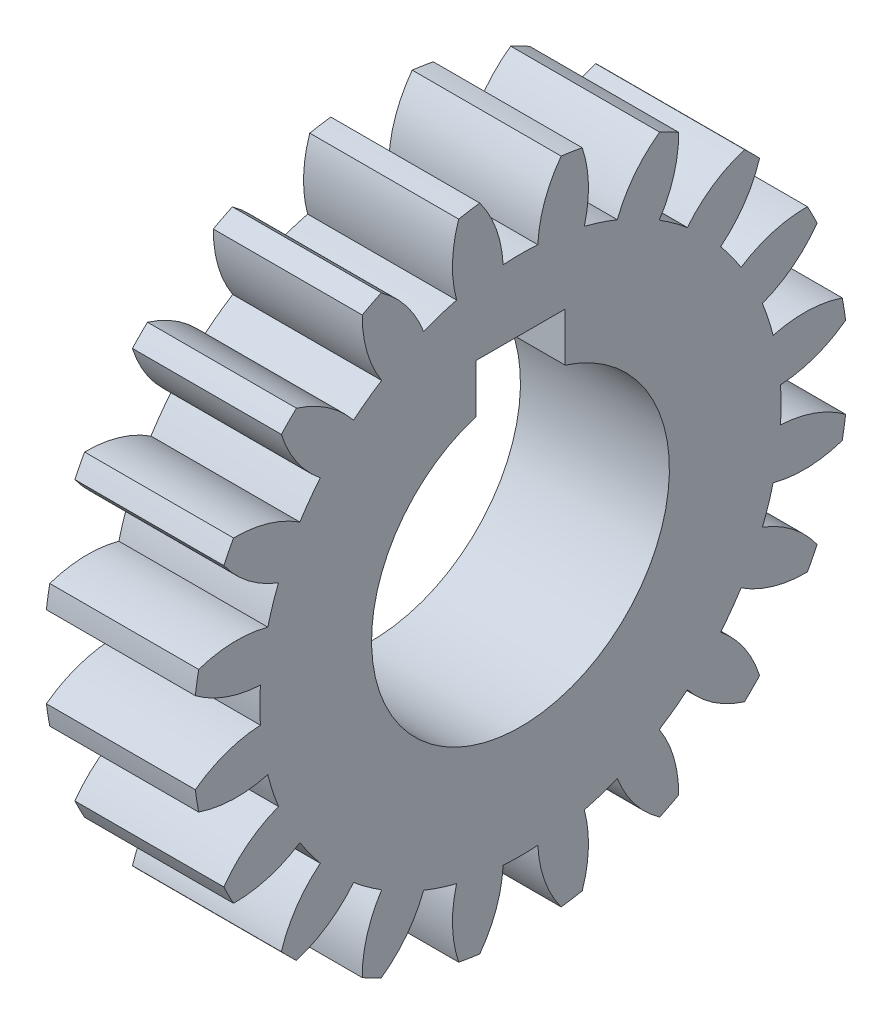
SolidWorks part; units mm, degrees
ref_plane "Plane1" through (0, 0, 0) normal (0, 0, 1) x (1, 0, 0)
ref_plane "Plane2" through (0, 0, 0) normal (0, 1, 0) x (1, 0, 0)
ref_plane "Plane3" through (0, 0, 0) normal (1, 0, 0) x (0, 0, -1)
sketch "HoldingSke" plane through (0, 0, 0) normal (0, 1, 0) x (1, 0, 0)
  line L0 (0, 0) -> (0.4698, -0.171)
  line L1 (-15, 0) -> (100, 0) construction
  line L2 (0, 0) -> (-2.1039, 2.3779)
  line L3 (0, 0) -> (-11.863, 4.5341)
  line L4 (0, 0) -> (8.1152, 2.9537)
  line L5 (0, 0) -> (-46.8476, -17.4728)
  line L6 (0, 0) -> (-8.2896, -5.593)
  line L7 (-2.1039, 2.3779) -> (8.6586, 51.2059)
  line L8 (-76.2, 54.61) -> (-73.4, 54.61)
  line L9 (-67.7845, 28.3722) -> (-49.3413, 33.142)
  line L10 (-76.2, 71.12) -> (104.1128, 71.12)
  line L11 (0, 0) -> (-10, 0)
  line L12 (-76.2, 101.6) -> (-76.133, 101.6)
  line L13 (24.9733, 27.94) -> (52.9518, 28.4284)
  line L14 (24.9733, 27.94) -> (24.9743, 27.94)
  line L15 (24.9733, 27.94) -> (100.4006, 29.5858)
  line L16 (-63.627, -2) -> (-12.827, -2)
  circle A0 centre (0, 0) radius 10
  circle A1 centre (0, 0) radius 17.499
  circle A2 centre (0, 0) radius 37.5
  circle A3 centre (0, 0) radius 10
  dimension "MHD" = 34.998
  dimension "Hub_dia" = 75
  dimension "Bore" = 20
  dimension "MBD" = 20
  dimension "Num_teeth" = 20
  dimension "Pitch" = 0.5
  dimension "Overall_len" = 50
  dimension "Show_teeth" = 20
  dimension "Thickness" = 10
  dimension "OAL" = 50.0001
  dimension "T_dim" = 2.8
  dimension "Ap" = 14.5
  dimension "H" = 19.05
  dimension "Pitch_radius" = 180.3128
  dimension "Width" = 10
  dimension "Backlash" = 0.067
  dimension "Addendum_fac" = 1
  dimension "Dedendum_fac" = 1.25
  dimension "Clearance_fac" = 0.25
  dimension "Dedendum_add" = 0.001
  dimension "Module" = 2
sketch "BasProSke" plane through (0, 0, 0) normal (0, 1, 0) x (1, 0, 0)
  line L0 (-10, 0) -> (60, 0) construction
  line L1 (0, 0) -> (0, 22)
  line L2 (0, 0) -> (10, 0)
  line L3 (10, 0) -> (10, 22)
  line L4 (10, 22) -> (0, 22)
  dimension "Thickness" = 10
  dimension "Diameter" = 44
revolve "Base-Revolve" add sketch "BasProSke" angle 360 about L0
sketch "TooCutSke" plane through (0, 0, 0) normal (1, 0, 0) x (0, 0, -1)
  line L1 (0, 0) -> (0, 107) construction
  line L2 (0, 0) -> (-1.6864, 19.9288) construction
  line L3 (0, 0) -> (-6.2409, 39.4033) construction
  line L4 (-1.6864, 19.9288) -> (-3.1204, 19.7016) construction
  arc A0 (1.165, 17.4602) -> (-1.165, 17.4602) centre (0, 0) ccw
  arc A1 (2.7485, 21.8532) -> (-2.7485, 21.8532) centre (0, 0) ccw
  circle A2 centre (0, 0) radius 20 construction
  circle A3 centre (0, 0) radius 19.363 construction
  arc A4 (-1.165, 17.4602) -> (-2.7485, 21.8532) centre (-9.1551, 17.0619) ccw
  arc A5 (2.7485, 21.8532) -> (1.165, 17.4602) centre (9.1551, 17.0619) ccw
  dimension "Root_dia" = 34.998
  dimension "Overcut_dia" = 44.0508
  dimension "Pitch_dia" = 40
  dimension "Base_dia" = 38.7259
  dimension "Flank_rad" = 8
  dimension "Half_ang" = 9
  dimension "Half_CT" = 1.4519
extrude "ToothCut" cut sketch "TooCutSke" along normal through all
fillet "Breaks" [suppressed] radius 0.04
fillet "RootFillets" [suppressed] radius 0.501
pattern_circular "TeethCuts" count 20 every 18 about axis through (-10, 0, 0) along (1, 0, 0) of "ToothCut", "RootFillets", "Breaks"
sketch "HubNeaOneSke" plane through (0, 0, 0) normal (-1, 0, 0) x (0, 0, 1)
  circle A0 centre (0, 0) radius 17.499
  dimension "Diameter" = 34.998
extrude "HubNearOne" [suppressed] add sketch "HubNeaOneSke" along normal blind 40.0001
sketch "HubNeaBotSke" plane through (0, 0, 0) normal (-1, 0, 0) x (0, 0, 1)
  circle A0 centre (0, 0) radius 17.499
  dimension "Diameter" = 34.998
extrude "HubNearBoth" [suppressed] add sketch "HubNeaBotSke" along normal blind 20
ref_plane "FarPln" through (10, 0, 0) normal (1, 0, 0) x (0, 0, -1)
sketch "HubFarSke" plane through (10, 0, 0) normal (1, 0, 0) x (0, 0, -1)
  circle A0 centre (0, 0) radius 17.499
  dimension "Diameter" = 34.998
extrude "HubFar" [suppressed] add sketch "HubFarSke" along normal blind 20
sketch "BorSke" plane through (0, 0, 0) normal (1, 0, 0) x (0, 0, -1)
  circle A0 centre (0, 0) radius 10
  dimension "Diameter" = 20
extrude "Bore" cut sketch "BorSke" along normal mid plane 100.0001
sketch "KeySke" plane through (0, 0, 0) normal (1, 0, 0) x (0, 0, -1)
  line L0 (-3, 0) -> (-3, 12.8)
  line L1 (-3, 12.8) -> (3, 12.8)
  line L2 (3, 12.8) -> (3, 0)
  line L3 (0, 0) -> (0, 34) construction
  line L4 (-3, 0) -> (3, 0)
  dimension "Offset" = 12.8
  dimension "Width" = 6
extrude "Keyway" cut sketch "KeySke" along normal mid plane 100.0001
pattern_circular "Keyway2" [suppressed] count 2 every 90 about axis through (-10, 0, 0) along (1, 0, 0)
equation "' \"Module@HoldingSke\" = 6.35"
equation "' \"Num_teeth@HoldingSke\" = 12"
equation "' \"Ap@HoldingSke\" =  20"
equation "' \"Ap@HoldingSke\" = 20"
equation "' \"Width@HoldingSke\" = 0.5 * 25.4"
equation "' \"Hub_dia@HoldingSke\"= 1 * 25.4"
equation "' \"Hub_dia@HoldingSke\" = 1 * 25.4"
equation "' \"Overall_len@HoldingSke\" = 1.0 * 25.4"
equation "' \"Bore@HoldingSke\" = 0.75 * 25.4"
equation "' \"T_dim@HoldingSke\" = 0.1 * 25.4"
equation "' \"Width@KeySke\" = 0.25 * 25.4"
equation "' \"Show_teeth@HoldingSke\" = 13"
equation "' \"Backlash@HoldingSke\" = 0.009 * 25.4"
equation "' \"Addendum_fac@HoldingSke\" = 1.0"
equation "' \"Dedendum_fac@HoldingSke\" = 1.25"
equation "' \"Dedendum_add@HoldingSke\" = 0.00005 * 25.4"
equation "' \"Clearance_fac@HoldingSke\" = 0.25"
equation "\"Pitch@HoldingSke\" = 1 / \"Module@HoldingSke\""
equation "\"Overcut_dia@TooCutSke\" = (\"Num_teeth@HoldingSke\" + 2 * \"Addendum_fac@HoldingSke\") / \"Pitch@HoldingSke\" + 0.002 * 25.4"
equation "\"Pitch_dia@TooCutSke\" = \"Num_teeth@HoldingSke\" / \"Pitch@HoldingSke\""
equation "\"Base_dia@TooCutSke\" = \"Num_teeth@HoldingSke\" / \"Pitch@HoldingSke\" * cos((\"Ap@HoldingSke\"  * 3.14159265 / 180))"
equation "\"Root_dia@TooCutSke\" = (\"Num_teeth@HoldingSke\" + 2) / \"Pitch@HoldingSke\" - 2 * (\"Addendum_fac@HoldingSke\" + \"Dedendum_fac@HoldingSke\") / \"Pitch@HoldingSke\" - \"Dedendum_add@HoldingSke\" * 2"
equation "\"Half_ang@TooCutSke\" = 180 / \"Num_teeth@HoldingSke\""
equation "\"Half_CT@TooCutSke\" = \"Num_teeth@HoldingSke\" / \"Pitch@HoldingSke\" * sin((3.14159265 / 2 / \"Num_teeth@HoldingSke\")) / 2 - 7 * \"Backlash@HoldingSke\" / 4"
equation "\"Flank_rad@TooCutSke\" = \"Num_teeth@HoldingSke\" / \"Pitch@HoldingSke\" / 5"
equation "\"Radius@RootFillets\" = \"Clearance_fac@HoldingSke\" / \"Pitch@HoldingSke\" + \"Dedendum_add@HoldingSke\""
equation "\"Break_rad@Breaks\" = 0.02 / \"Pitch@HoldingSke\""
equation "\"Thickness@HoldingSke\" = \"Width@HoldingSke\""
equation "\"OAL@HoldingSke\" = \"Thickness@HoldingSke\""
equation "\"MHD@HoldingSke\" = (\"Num_teeth@HoldingSke\" + 2) / \"Pitch@HoldingSke\" - 2 * (\"Addendum_fac@HoldingSke\" + \"Dedendum_fac@HoldingSke\")  / \"Pitch@HoldingSke\" - \"Dedendum_add@HoldingSke\" * 2"
equation "\"MBD@HoldingSke\" = (\"Num_teeth@HoldingSke\" + 2) / \"Pitch@HoldingSke\" - 2 * (\"Addendum_fac@HoldingSke\" + \"Dedendum_fac@HoldingSke\")  / \"Pitch@HoldingSke\" - \"Dedendum_add@HoldingSke\" * 2 - 0.002 * 25.4"
equation "\"MHD@HoldingSke\" = ((sgn( \"MHD@HoldingSke\" - \"Hub_dia@HoldingSke\" )-1)*( \"MHD@HoldingSke\" - \"Hub_dia@HoldingSke\" ))/-2+ \"Hub_dia@HoldingSke\""
equation "\"MBD@HoldingSke\" = ((sgn( \"MBD@HoldingSke\" - \"Bore@HoldingSke\" )-1)*( \"MBD@HoldingSke\" - \"Bore@HoldingSke\" ))/-2+ \"Bore@HoldingSke\""
equation "\"OAL@HoldingSke\" = ((sgn( \"OAL@HoldingSke\" - \"Overall_len@HoldingSke\" )+1)*( \"OAL@HoldingSke\" - \"Overall_len@HoldingSke\" ))/2 + \"Overall_len@HoldingSke\" + 0.000002 * 25.4"
equation "\"Num_teeth@TeethCuts\" = int( \"Show_teeth@HoldingSke\" ) + 1"
equation "\"Num_teeth@TeethCuts\" = ((sgn( \"Num_teeth@TeethCuts\" - \"Num_teeth@HoldingSke\" )-1)*( \"Num_teeth@TeethCuts\" - \"Num_teeth@HoldingSke\" ))/-2+ \"Num_teeth@HoldingSke\""
equation "\"Num_teeth@TeethCuts\" = ((sgn( \"Num_teeth@TeethCuts\" - 2.0)+1)*( \"Num_teeth@TeethCuts\" - 2.0))/2 +2.0"
equation "\"Angle@TeethCuts\" = 360.0 / \"Num_teeth@HoldingSke\""
equation "\"Diameter@BasProSke\" = (\"Num_teeth@HoldingSke\" + 2 * \"Addendum_fac@HoldingSke\") / \"Pitch@HoldingSke\""
equation "\"Thickness@BasProSke\"  = \"Thickness@HoldingSke\""
equation "' \"Fillet_rad@BasProSke\" =  \"Thickness@HoldingSke\" * 0.05"
equation "' \"Fillet_rad@BasProSke\" = \"Thickness@HoldingSke\" * 0.05"
equation "\"MHD@HoldingSke\" = ((sgn( \"MHD@HoldingSke\" - \"Root_dia@TooCutSke\" )-1)*( \"MHD@HoldingSke\" - \"Root_dia@TooCutSke\" ))/-2+ \"Root_dia@TooCutSke\""
equation "\"Diameter@HubNeaOneSke\" = \"MHD@HoldingSke\""
equation "\"Length@HubNearOne\" = \"OAL@HoldingSke\" - \"Thickness@BasProSke\""
equation "\"Diameter@HubNeaBotSke\" = \"MHD@HoldingSke\""
equation "\"Length@HubNearBoth\" = ( \"OAL@HoldingSke\" - \"Thickness@BasProSke\" ) / 2.0"
equation "\"Thickness@FarPln\" = \"Thickness@BasProSke\""
equation "\"Diameter@HubFarSke\" = \"MHD@HoldingSke\""
equation "\"Length@HubFar\" = ( \"OAL@HoldingSke\" - \"Thickness@BasProSke\" ) / 2.0"
equation "\"Diameter@BorSke\" = \"MBD@HoldingSke\""
equation "\"D1@Bore\" = \"OAL@HoldingSke\" * 2.0"
equation "\"D1@Keyway\" = \"OAL@HoldingSke\" * 2.0"
equation "\"Offset@KeySke\" = \"T_dim@HoldingSke\" + \"MBD@HoldingSke\" / 2.0"
